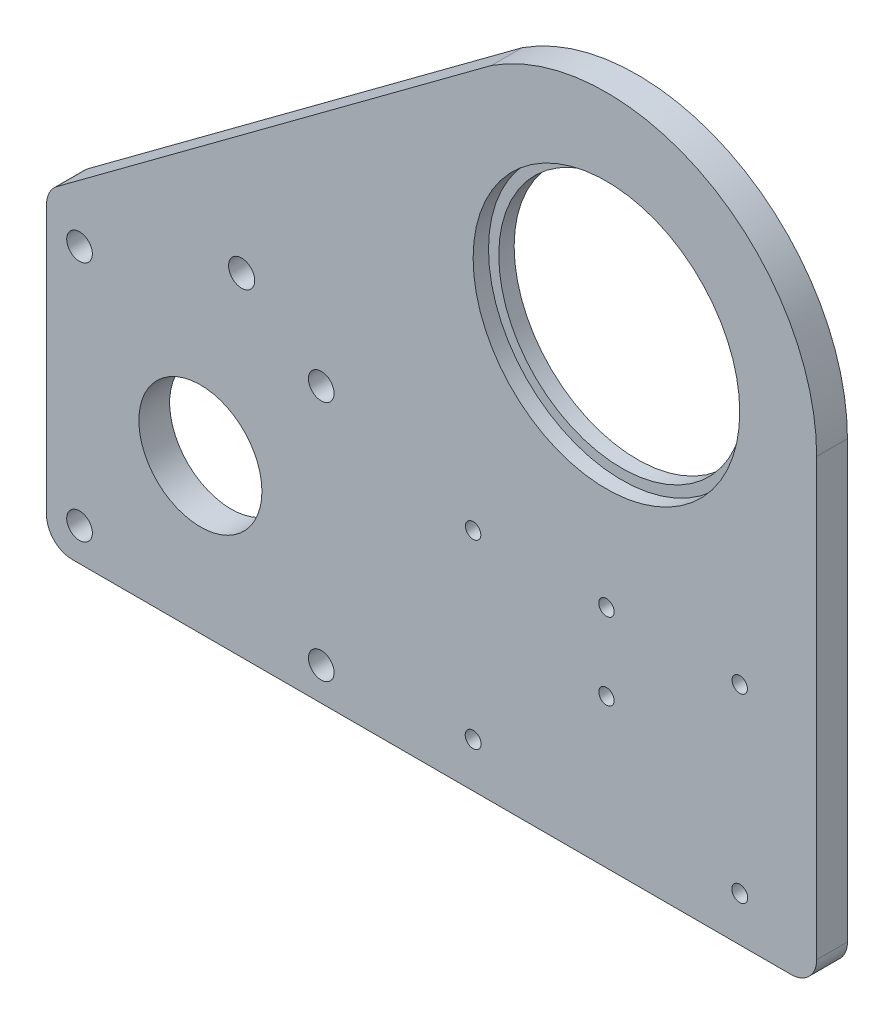
SolidWorks part; units mm, degrees
material "3003 Alloy"
ref_plane "Front Plane" through (0, 0, 0) normal (0, 0, 1) x (1, 0, 0)
ref_plane "Top Plane" through (0, 0, 0) normal (0, 1, 0) x (1, 0, 0)
ref_plane "Right Plane" through (0, 0, 0) normal (1, 0, 0) x (0, 0, -1)
sketch "Sketch1" plane through (0, 0, 0) normal (0, 0, 1) x (1, 0, 0)
  line L0 (-30, 30) -> (56.7747, 94.3295)
  line L1 (120.1876, 59.9978) -> (120.1876, -30)
  line L2 (30, -30) -> (-30, -30)
  line L3 (30, -30) -> (30, 30)
  line L4 (30, 30) -> (-30, 30)
  line L5 (-30, -30) -> (-30, 30)
  line L6 (30, -30) -> (-30, 30) construction
  line L7 (30, 30) -> (-30, -30) construction
  line L8 (120.1876, -30) -> (30, -30)
  circle A0 centre (0, 0) radius 4
  circle A1 centre (79.1876, 59.9978) radius 26
  circle A3 centre (79.1876, 59.9978) radius 41
extrude "Boss-Extrude1" add sketch "Sketch1" along normal blind 10 contours A3 L0 L4 L3 L8 L1 | L5 L2 L3 L4 A0 | A3 L0 A1
fillet "Fillet1" radius 5 3 edges at (120.1876, -30, 5) (-30, 30, 5) (-30, -30, 5)
sketch "Sketch3" plane through (0, 0, 0) normal (0, 0, -1) x (-1, 0, 0)
  circle A0 centre (-79.1876, 59.9978) radius 26 construction
  circle A1 centre (-79.1876, 59.9978) radius 26
  circle A2 centre (-79.1876, 59.9978) radius 24
  dimension "D1" = 2
extrude "Boss-Extrude2" add sketch "Sketch3" against normal blind 3
sketch "Sketch4" plane through (0, 0, 10) normal (0, 0, 1) x (1, 0, 0)
  circle A0 centre (0, 0) radius 20
extrude "Cut-Extrude1" cut sketch "Sketch4" against normal blind 1.6
sketch "Sketch5" plane through (0, 0, 8.4) normal (0, 0, 1) x (1, 0, 0)
  circle A0 centre (0, 0) radius 8
extrude "Cut-Extrude2" cut sketch "Sketch5" against normal through all
sketch "Sketch6" plane through (0, 0, 10) normal (0, 0, 1) x (1, 0, 0)
  circle A0 centre (23.57, 23.57) radius 2.5
  circle A1 centre (-23.57, 23.57) radius 2.5
  circle A2 centre (-23.57, -23.57) radius 2.5
  circle A3 centre (23.57, -23.57) radius 2.5
extrude "Cut-Extrude3" cut sketch "Sketch6" against normal through all
sketch "Sketch8" plane through (0, 0, 8.4) normal (0, 0, 1) x (1, 0, 0)
  circle A0 centre (0, 0) radius 12
extrude "Cut-Extrude5" cut sketch "Sketch8" against normal through all
sketch "Sketch9" plane through (0, 0, 10) normal (0, 0, 1) x (1, 0, 0)
  line L4 (-25, -30) -> (115.1876, -30)
  line L5 (120.1876, -25) -> (120.1876, 59.9978)
  line L6 (56.7747, 94.3295) -> (-27.9777, 31.4992)
  line L7 (-30, 27.4826) -> (-30, -25)
  line L8 (-25, -30) -> (115.1876, -30)
  line L9 (120.1876, -25) -> (120.1876, 59.9978)
  line L10 (56.7747, 94.3295) -> (-27.9777, 31.4992)
  line L11 (-30, 27.4826) -> (-30, -25)
  circle A0 centre (0, 0) radius 12 construction
  circle A1 centre (0, 0) radius 12
  arc A3 (115.1876, -30) -> (120.1876, -25) centre (115.1876, -25) ccw
  arc A4 (120.1876, 59.9978) -> (56.7747, 94.3295) centre (79.1876, 59.9978) ccw
  arc A5 (-27.9777, 31.4992) -> (-30, 27.4826) centre (-25, 27.4826) ccw
  arc A6 (115.1876, -30) -> (120.1876, -25) centre (115.1876, -25) ccw
  arc A7 (120.1876, 59.9978) -> (56.7747, 94.3295) centre (79.1876, 59.9978) ccw
  arc A8 (-27.9777, 31.4992) -> (-30, 27.4826) centre (-25, 27.4826) ccw
  arc A12 (-30, -25) -> (-25, -30) centre (-25, -25) ccw
  arc A13 (-30, -25) -> (-25, -30) centre (-25, -25) ccw
  dimension "D1" = 0
extrude "Cut-Extrude6" cut sketch "Sketch9" against normal blind 4
sketch "Sketch10" plane through (0, 0, 6) normal (0, 0, 1) x (1, 0, 0)
  circle A2 centre (53.1876, -16.0022) radius 1.5
  circle A3 centre (105.1876, -16.0022) radius 1.5
  circle A4 centre (105.1876, 13.9978) radius 1.5
  circle A5 centre (79.1876, -1.0022) radius 1.5
  circle A6 centre (53.1876, 13.9978) radius 1.5
  circle A7 centre (79.1876, 13.9978) radius 1.5
extrude "Cut-Extrude7" cut sketch "Sketch10" against normal through all
sketch "Sketch11" plane through (0, 0, 6) normal (0, 0, 1) x (1, 0, 0)
  circle A0 centre (53.1876, -21.3) radius 1.55
  circle A1 centre (105.1876, -21.3) radius 1.55
extrude "Cut-Extrude8" cut sketch "Sketch11" against normal through all
sketch "Sketch12" plane through (0, 0, 6) normal (0, 0, 1) x (1, 0, 0)
  circle A0 centre (53.1876, -16.0022) radius 1.5
  circle A1 centre (105.1876, -16.0022) radius 1.5
extrude "Boss-Extrude3" add sketch "Sketch12" against normal blind 6
sketch "Sketch13" plane through (0, 0, 0) normal (0, 0, -1) x (-1, 0, 0)
  circle A2 centre (-8.0439, 34.8874) radius 2.55
extrude "Cut-Extrude9" cut sketch "Sketch13" against normal through all
